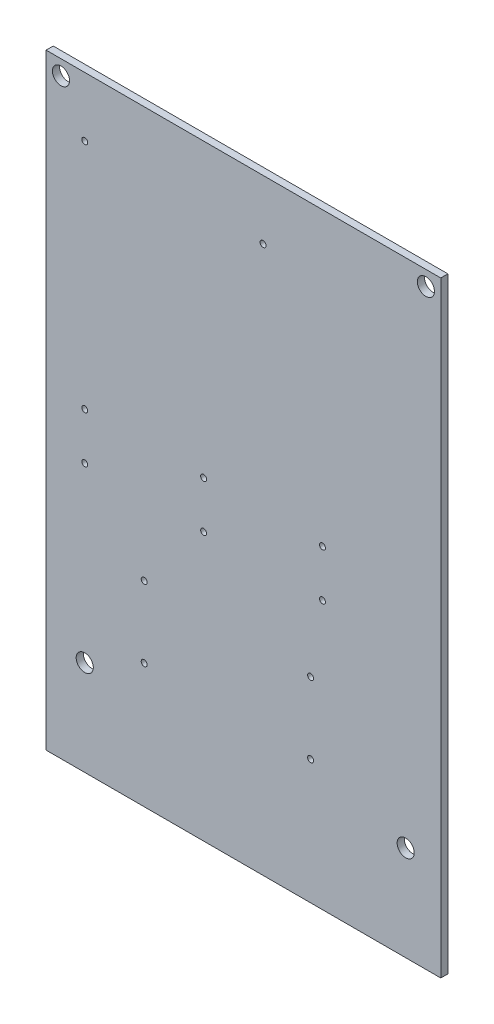
SolidWorks part; units mm, degrees
ref_plane "Front Plane" through (0, 0, 0) normal (0, 0, 1) x (1, 0, 0)
ref_plane "Top Plane" through (0, 0, 0) normal (0, 1, 0) x (1, 0, 0)
ref_plane "Right Plane" through (0, 0, 0) normal (1, 0, 0) x (0, 0, -1)
sketch "Sketch1" plane through (0, 0, 0) normal (0, 0, 1) x (1, 0, 0)
  line L1 (-42.164, -82.55) -> (42.164, -82.55)
  line L2 (-42.164, -82.55) -> (-42.164, 82.55)
  line L3 (-42.164, 82.55) -> (42.164, 82.55)
  line L4 (42.164, -82.55) -> (42.164, 82.55)
  line L5 (-42.164, -82.55) -> (42.164, 82.55) construction
  line L6 (-42.164, 82.55) -> (42.164, -82.55) construction
  circle A0 centre (-38.989, 79.375) radius 1.8288
  circle A1 centre (38.989, 79.375) radius 1.8288
  circle A2 centre (-38.989, -79.375) radius 1.8288
  circle A3 centre (38.989, -79.375) radius 1.8288
  circle A4 centre (-33.909, -26.67) radius 1.8288
  circle A5 centre (34.671, -26.67) radius 1.8288
  point P0 (0, 0)
  dimension "D4" = 3.6576
  dimension "D5" = 3.6576
  dimension "D6" = 3.6576
  dimension "D7" = 3.6576
  dimension "D8" = 3.6576
  dimension "D9" = 3.6576
  dimension "D11" = 109.22
  dimension "D1" = 165.1
  dimension "D2" = 84.328
  dimension "D3" = 3.175
  dimension "D10" = 3.175
  dimension "D12" = 3.175
  dimension "D13" = 3.175
  dimension "D14" = 8.255
  dimension "D15" = 68.58
extrude "Extrude1" add sketch "Sketch1" along normal blind 1.524
sketch "Sketch3" plane through (0, 0, 1.524) normal (0, 0, 1) x (1, 0, 0)
  line L0 (42.164, 82.55) -> (-42.164, 82.55) construction
  line L1 (-42.164, 82.55) -> (-42.164, -82.55) construction
  circle A0 centre (-33.909, 69.85) radius 0.635
  circle A1 centre (4.191, 69.85) radius 0.635
  dimension "D1" = 1.27
  dimension "D2" = 12.7
  dimension "D3" = 8.255
  dimension "D4" = 38.1
extrude "LCD holes" cut sketch "Sketch3" against normal through all
sketch "Sketch4" plane through (0, 0, 1.524) normal (0, 0, 1) x (1, 0, 0)
  line L0 (-28.6703, 14.9225) -> (33.3692, 14.9225) construction
  circle A0 centre (-33.909, 20.24) radius 0.635
  circle A1 centre (-21.5265, 14.9225) radius 7.1437 construction
  circle A2 centre (-33.909, 10.24) radius 0.635
  circle A3 centre (-8.509, 10.24) radius 0.635
  circle A4 centre (-8.509, 20.24) radius 0.635
  circle A5 centre (16.891, 10.24) radius 0.635
  circle A6 centre (16.891, 20.24) radius 0.635
  circle A7 centre (26.2255, 14.9225) radius 7.1438 construction
  dimension "D1" = 1.27
  dimension "D3" = 1.27
  dimension "D4" = 10
  dimension "D5" = 25.4
  dimension "D6" = 25.4
extrude "Pot Holes" cut sketch "Sketch4" against normal through all
sketch "Sketch5" plane through (0, 0, 1.524) normal (0, 0, 1) x (1, 0, 0)
  circle A0 centre (-21.209, -5.16) radius 0.635
  circle A1 centre (-33.909, 20.24) radius 0.635 construction
  circle A2 centre (14.351, -5.16) radius 0.635
  circle A3 centre (-21.209, -20.4) radius 0.635
  circle A4 centre (14.351, -20.4) radius 0.635
  dimension "D1" = 1.27
  dimension "D2" = 25.4
  dimension "D3" = 12.7
  dimension "D4" = 15.24
  dimension "D5" = 35.56
extrude "Arduino Header holes" cut sketch "Sketch5" against normal through all
sketch "Sketch6" plane through (0, 0, 1.524) normal (0, 0, 1) x (1, 0, 0)
  line L0 (-42.164, 82.55) -> (-42.164, -82.55) construction
  line L1 (-42.164, -46.99) -> (42.164, -46.99)
  line L2 (-42.164, -46.99) -> (-42.164, -82.55)
  line L3 (-42.164, -82.55) -> (42.164, -82.55)
  line L4 (42.164, -46.99) -> (42.164, -82.55)
  line L5 (-54.864, -46.99) -> (249.936, -46.99) construction
extrude "Cut-Extrude1" cut sketch "Sketch6" against normal through all
